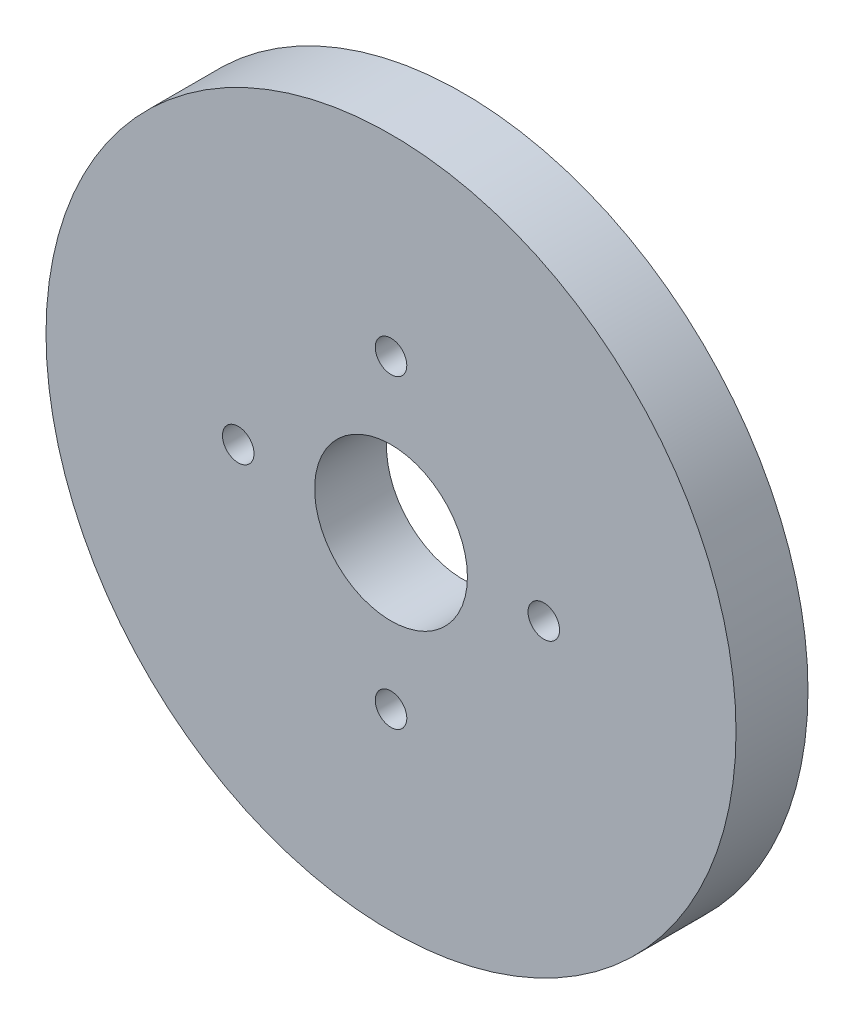
SolidWorks part; units mm, degrees
ref_plane "Front Plane" through (0, 0, 0) normal (0, 0, 1) x (1, 0, 0)
ref_plane "Top Plane" through (0, 0, 0) normal (0, 1, 0) x (1, 0, 0)
ref_plane "Right Plane" through (0, 0, 0) normal (1, 0, 0) x (0, 0, -1)
sketch "Sketch1" plane through (0, 0, 0) normal (0, 0, 1) x (1, 0, 0)
  line L0 (0, 1.8499) -> (0, 50001.8499) construction
  line L1 (0, 0) -> (-50000, 0) construction
  circle A0 centre (0, 0) radius 17.5
  circle A1 centre (0, 0) radius 3.875
  circle A2 centre (7.75, 0) radius 0.8
  circle A4 centre (0, 7.75) radius 0.8
  circle A5 centre (-7.75, 0) radius 0.8
  circle A6 centre (0, -7.75) radius 0.8
  dimension "D1" = 35
  dimension "D2" = 7.75
  dimension "D3" = 1.6
  dimension "D4" = 7.75
  dimension "D5" = 7.75
extrude "Boss-Extrude1" add sketch "Sketch1" along normal mid plane 3.65
